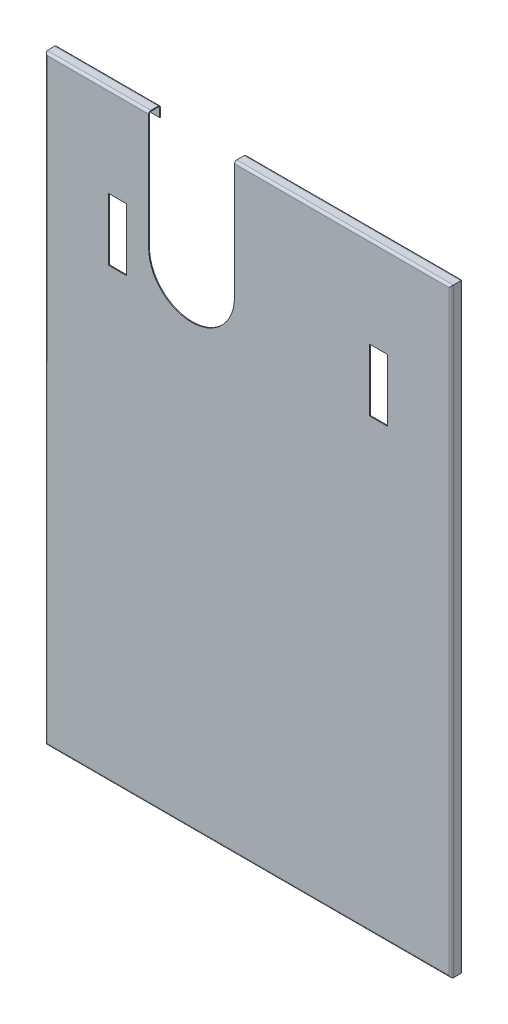
SolidWorks part; units mm, degrees
ref_plane "정면" through (0, 0, 0) normal (0, 0, 1) x (1, 0, 0)
ref_plane "윗면" through (0, 0, 0) normal (0, 1, 0) x (1, 0, 0)
ref_plane "우측면" through (0, 0, 0) normal (1, 0, 0) x (0, 0, -1)
sketch "스케치1" plane through (0, 0, 0) normal (0, 0, 1) x (1, 0, 0)
  line L1 (0, 0) -> (568, 0)
  line L2 (0, 0) -> (0, 839)
  line L3 (0, 839) -> (568, 839)
  line L4 (568, 0) -> (568, 839)
  line L5 (89, 712) -> (114, 712)
  line L6 (89, 712) -> (89, 625)
  line L7 (89, 625) -> (114, 625)
  line L8 (114, 712) -> (114, 625)
  line L9 (454, 712) -> (479, 712)
  line L10 (454, 712) -> (454, 625)
  line L11 (454, 625) -> (479, 625)
  line L12 (479, 712) -> (479, 625)
  point P14 (114, 668.5)
  dimension "D1" = 839
  dimension "D2" = 568
  dimension "D3" = 89
  dimension "D4" = 25
  dimension "D5" = 340
  dimension "D6" = 25
  dimension "D7" = 87
  dimension "D8" = 625
extrude "보스-돌출1" add sketch "스케치1" along normal blind 1.2
sketch "스케치2" plane through (0, 0, 0) normal (0, 0, -1) x (-1, 0, 0)
  line L0 (-1.2, 837.8) -> (-566.8, 837.8)
  line L1 (-566.8, 837.8) -> (-566.8, 1.2)
  line L2 (-566.8, 1.2) -> (-1.2, 1.2)
  line L3 (-1.2, 1.2) -> (-1.2, 837.8)
  line L4 (0, 0) -> (0, 839)
  line L5 (0, 839) -> (-568, 839)
  line L6 (-568, 839) -> (-568, 0)
  line L7 (-568, 0) -> (0, 0)
  line L8 (0, 0) -> (0, 839)
  line L9 (0, 839) -> (-568, 839)
  line L10 (-568, 839) -> (-568, 0)
  line L11 (-568, 0) -> (0, 0)
  dimension "D1" = 0
  dimension "D2" = 1.2
extrude "보스-돌출2" add sketch "스케치2" along normal blind 15.5
sketch "스케치3" plane through (0, 0, -15.5) normal (0, 0, -1) x (-1, 0, 0)
  line L0 (-15, 824) -> (-553, 824)
  line L1 (-553, 824) -> (-553, 15)
  line L2 (-553, 15) -> (-15, 15)
  line L3 (-15, 15) -> (-15, 824)
  line L4 (-568, 0) -> (0, 0)
  line L5 (0, 0) -> (0, 839)
  line L6 (0, 839) -> (-568, 839)
  line L7 (-568, 839) -> (-568, 0)
  line L8 (-568, 0) -> (0, 0)
  line L9 (0, 0) -> (0, 839)
  line L10 (0, 839) -> (-568, 839)
  line L11 (-568, 839) -> (-568, 0)
  dimension "D1" = 0
  dimension "D2" = 15
extrude "보스-돌출3" add sketch "스케치3" against normal blind 1.2
fillet "필렛1" radius 2 12 edges at (566.8, 419.5, 0) (566.8, 419.5, -14.3) (284, 1.2, 0) (284, 1.2, -14.3) (566.8, 1.2, -7.15) (1.2, 419.5, 0) (1.2, 419.5, -14.3) (1.2, 1.2, -7.15) (284, 837.8, 0) (566.8, 837.8, -7.15) (284, 837.8, -14.3) (1.2, 837.8, -7.15)
fillet "필렛2" radius 3.2 4 edges at (284, 839, 1.2) (284, 0, 1.2) (0, 419.5, 1.2) (568, 419.5, 1.2)
fillet "필렛3" radius 3.2 4 edges at (568, 419.5, -15.5) (284, 839, -15.5) (0, 419.5, -15.5) (284, 0, -15.5)
sketch "스케치4" plane through (0, 0, 1.2) normal (0, 0, 1) x (1, 0, 0)
  line L0 (205, 952.2572) -> (205, 674) construction
  line L1 (265, 952.2572) -> (265, 674)
  line L2 (145, 952.2572) -> (145, 674)
  line L3 (0, 839) -> (568, 839) construction
  line L5 (0, 0) -> (0, 839) construction
  arc A0 (265, 952.2572) -> (145, 952.2572) centre (205, 952.2572) ccw
  arc A1 (145, 674) -> (265, 674) centre (205, 674) ccw
  point P2 (205, 813.1286)
  dimension "D1" = 60
  dimension "D2" = 165
  dimension "D3" = 145
extrude "컷-돌출1" cut sketch "스케치4" against normal through all
